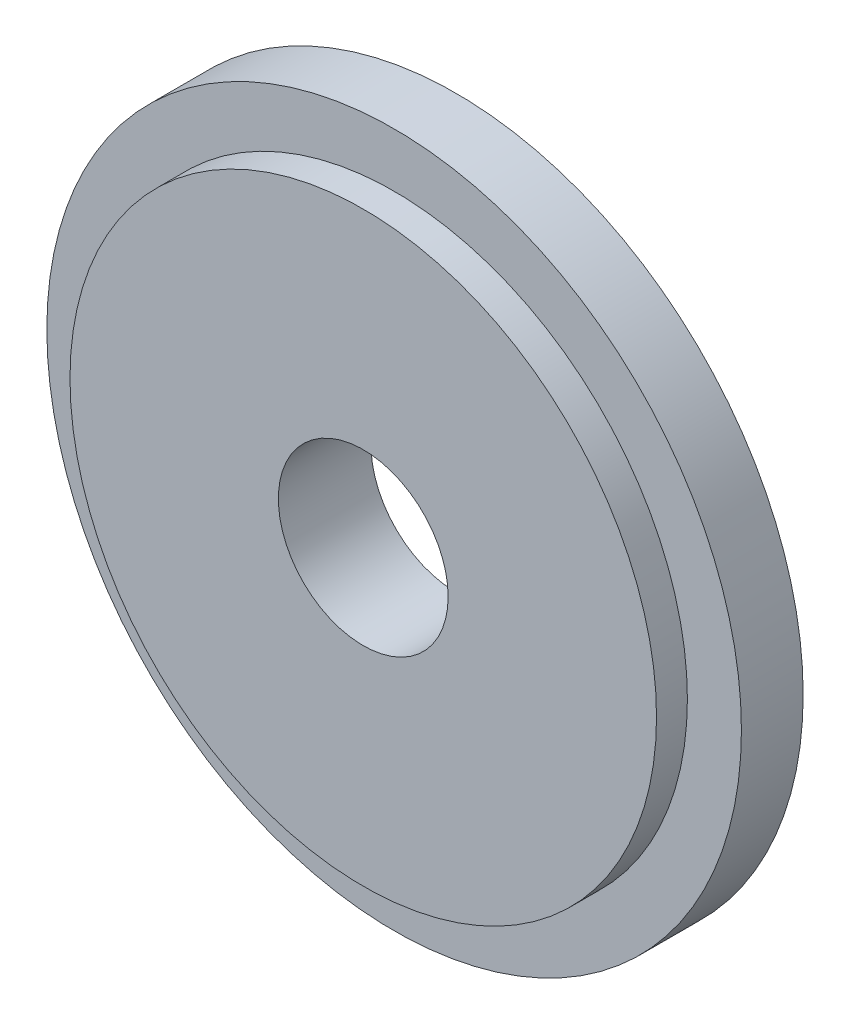
SolidWorks part; units mm, degrees
ref_plane "前视基准面" through (0, 0, 0) normal (0, 0, 1) x (1, 0, 0)
ref_plane "上视基准面" through (0, 0, 0) normal (0, 1, 0) x (1, 0, 0)
ref_plane "右视基准面" through (0, 0, 0) normal (1, 0, 0) x (0, 0, -1)
sketch "草图1" plane through (0, 0, 0) normal (0, 0, 1) x (1, 0, 0)
  circle A0 centre (0, 0) radius 22.5
  dimension "D1" = 45
extrude "拉伸1" add sketch "草图1" along normal blind 4
sketch "草图2" plane through (0, 0, 4) normal (0, 0, 1) x (1, 0, 0)
  circle A0 centre (0, 0) radius 19
  dimension "D1" = 38
extrude "拉伸2" add sketch "草图2" along normal blind 2
sketch "草图3" plane through (0, 0, 6) normal (0, 0, 1) x (1, 0, 0)
  circle A0 centre (0, 0) radius 5.5
  dimension "D1" = 11
extrude "拉伸3" cut sketch "草图3" against normal through all
